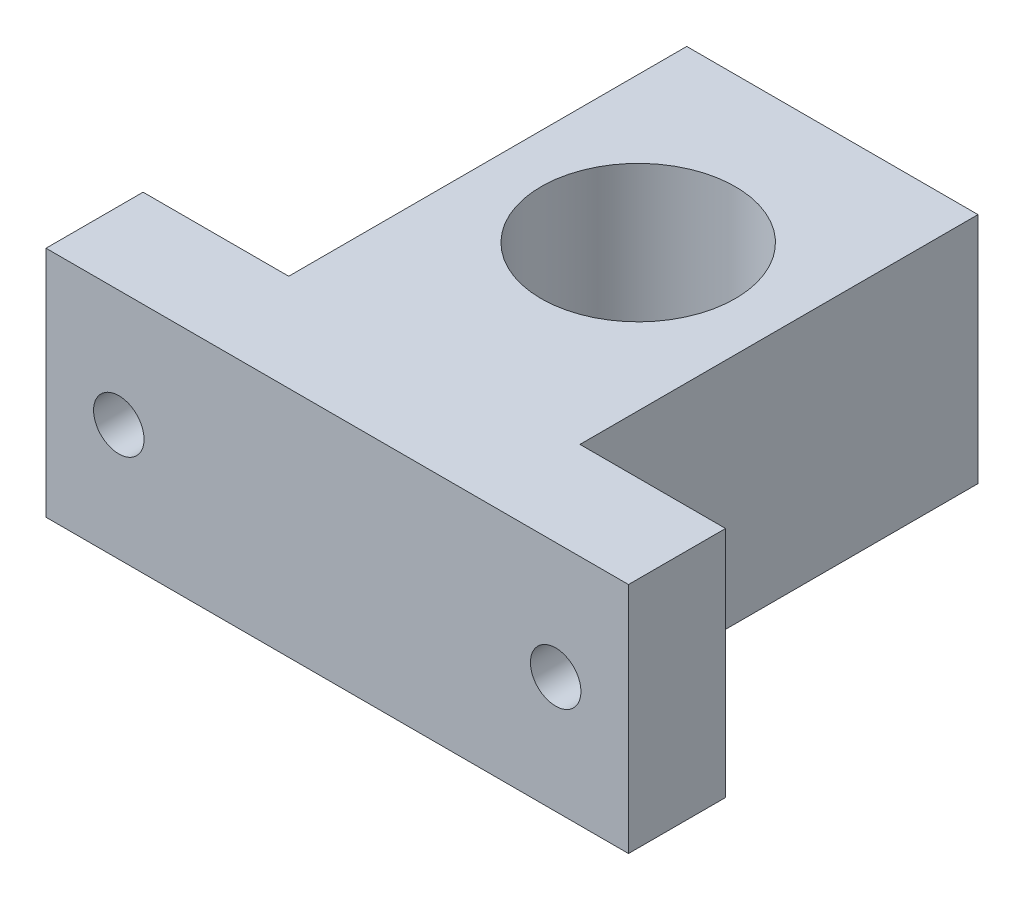
SolidWorks part; units mm, degrees
ref_plane "前视基准面" through (0, 0, 0) normal (0, 0, 1) x (1, 0, 0)
ref_plane "上视基准面" through (0, 0, 0) normal (0, 1, 0) x (1, 0, 0)
ref_plane "右视基准面" through (0, 0, 0) normal (1, 0, 0) x (0, 0, -1)
sketch "草图1" plane through (0, 0, 0) normal (0, 1, 0) x (1, 0, 0)
  line L0 (30, 0) -> (-30, 0)
  line L1 (-30, 0) -> (-30, 10)
  line L2 (-30, 10) -> (-15, 10)
  line L3 (-15, 10) -> (-15, 51)
  line L4 (-15, 51) -> (15, 51)
  line L5 (0, 57.9337) -> (0, -31.5239) construction
  line L6 (15, 10) -> (15, 51)
  line L7 (30, 10) -> (15, 10)
  line L8 (30, 0) -> (30, 10)
  circle A0 centre (0, 31) radius 10
  point P11 (0, 51)
  point P12 (0, 0)
  dimension "D5" = 20
  dimension "D6" = 31
  dimension "D1" = 60
  dimension "D2" = 10
  dimension "D3" = 30
  dimension "D4" = 51
extrude "凸台-拉伸1" add sketch "草图1" along normal blind 24
sketch "草图2" plane through (0, 0, -10) normal (0, 0, -1) x (-1, 0, 0)
  line L0 (-30, 12) -> (42.2085, 12) construction
  line L1 (-30, 24) -> (-30, 0) construction
  line L2 (0, 24) -> (0, -12.3652) construction
  line L3 (-15, 24) -> (15, 24) construction
  circle A0 centre (-22.5, 12) radius 2.6
  circle A1 centre (22.5, 12) radius 2.6
  dimension "D1" = 5.2
  dimension "D2" = 45
extrude "切除-拉伸1" cut sketch "草图2" against normal blind 24
